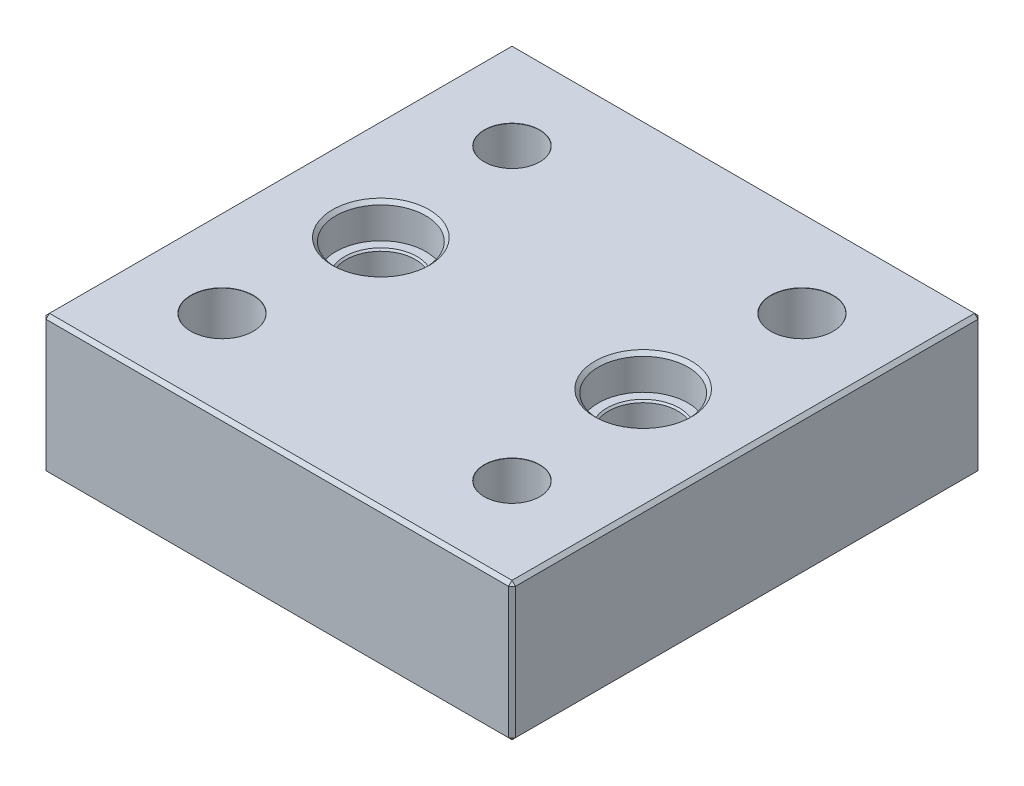
SolidWorks part; units mm, degrees
material "Plain Carbon Steel"
ref_plane "Front Plane" through (0, 0, 0) normal (0, 0, 1) x (1, 0, 0)
ref_plane "Top Plane" through (0, 0, 0) normal (0, 1, 0) x (1, 0, 0)
ref_plane "Right Plane" through (0, 0, 0) normal (1, 0, 0) x (0, 0, -1)
sketch "Sketch1" plane through (0, 0, 0) normal (0, 1, 0) x (1, 0, 0)
  line L1 (-34, 34) -> (34, 34)
  line L2 (-34, 34) -> (-34, -34)
  line L3 (-34, -34) -> (34, -34)
  line L4 (34, 34) -> (34, -34)
  line L5 (-34, 34) -> (34, -34) construction
  line L6 (-34, -34) -> (34, 34) construction
  point P0 (0, 0)
  dimension "D1" = 68
  dimension "D2" = 68
extrude "Boss-Extrude1" add sketch "Sketch1" against normal blind 20
sketch "Sketch2" plane through (0, 0, 0) normal (0, 1, 0) x (1, 0, 0)
  line L0 (-34, 0) -> (34, 0) construction
  line L1 (-34, 34) -> (-34, -34) construction
  line L2 (34, -34) -> (34, 34) construction
  line L3 (-34, -34) -> (34, -34) construction
  line L4 (0, 34) -> (0, -34) construction
  line L5 (34, 34) -> (-34, 34) construction
  circle A0 centre (-19, 0) radius 5
  circle A1 centre (19, 0) radius 5
  dimension "D2" = 10
  dimension "D1" = 38
extrude "Cut-Extrude1" cut sketch "Sketch2" against normal up to next
sketch "Sketch3" plane through (0, 0, 0) normal (0, 1, 0) x (1, 0, 0)
  circle A0 centre (-19, 0) radius 6.5
  circle A1 centre (19, 0) radius 6.5
  dimension "D1" = 13
extrude "Cut-Extrude2" cut sketch "Sketch3" against normal blind 5
chamfer "Chamfer2" distance 0.5 angle 45 12 edges at (34, -10, -34) (34, -20, 0) (0, -20, -34) (-34, -10, -34) (34, -10, 34) (0, -20, 34) (-34, -20, 0) (-34, -10, 34) (-34, 0, 0) (0, 0, 34) (34, 0, 0) (0, 0, -34)
chamfer "Chamfer4" distance 0.5 angle 45 2 edges at (19, 0, 6.5) (-19, 0, 6.5)
chamfer "Chamfer5" distance 0.25 angle 45 4 edges at (19, -20, 5) (-19, -20, 5) (19, -5, 5) (-19, -5, 5)
hole_wizard "CBORE for M8 Hex Socket Head Cap Screw1" positions "Sketch4" profile "Sketch5" counterbore size "M8" standard "ISO" end condition through all
sketch "Sketch4" plane through (0, -20, 0) normal (0, -1, 0) x (-1, 0, 0)
  line L0 (-34, -33.5) -> (-34, 33.5) construction
  line L1 (-33.5, 34) -> (33.5, 34) construction
  line L4 (34, 33.5) -> (34, -33.5) construction
  line L5 (33.5, -34) -> (-33.5, -34) construction
  point P2 (21, -21)
  point P6 (-21, 21)
  dimension "D1" = 13
  dimension "D2" = 13
  dimension "D3" = 13
  dimension "D4" = 13
sketch "Sketch5" plane through (-21, -20, 21) normal (1, 0, 0) x (0, 0, -1)
  line L0 (0, 0) -> (0, 20)
  line L1 (4.5, 19.975) -> (4.525, 20)
  line L2 (7.5, 8.6) -> (4.5, 8.6)
  line L3 (4.5, 8.6) -> (4.5, 19.975)
  line L5 (7.5, 8.6) -> (7.5, 0.025)
  line L6 (7.5, 0.025) -> (7.525, 0)
  line L7 (7.525, 0) -> (0, 0)
  line L8 (-7.5, 0.025) -> (-7.525, 0) construction
  line L11 (0, -6.35) -> (0, 107.95) construction
  line L12 (4.525, 20) -> (0, 20)
  line L13 (-4.5, 19.975) -> (-4.525, 20) construction
  dimension "Thru Hole Dia." = 9
  dimension "Thru Hole Depth" = 20
  dimension "C'Bore Dia." = 15
  dimension "C'Bore Depth" = 8.6
  dimension "Near C'Sink Dia." = 15.05
  dimension "Near C'Sink Angle" = 90
  dimension "Far C'Sink Dia." = 9.05
  dimension "Far C'Sink Angle" = 90
sketch "Sketch6" plane through (0, -20, 0) normal (0, -1, 0) x (-1, 0, 0)
  line L0 (-33.5, 34) -> (33.5, 34) construction
  line L1 (34, 33.5) -> (34, -33.5) construction
  line L2 (33.5, -34) -> (-33.5, -34) construction
  line L3 (-34, -33.5) -> (-34, 33.5) construction
  point P0 (21, 21)
  point P2 (-21, -21)
  dimension "D1" = 13
  dimension "D2" = 13
  dimension "D3" = 13
  dimension "D4" = 13
hole_wizard "Ø8.0mm Dowel Hole1" positions "Sketch6" profile "Sketch7" hole size "Ø8.0" standard "ISO" end condition through all
sketch "Sketch7" plane through (-21, -20, -21) normal (1, 0, 0) x (0, 0, -1)
  line L0 (0, 0) -> (0, 20)
  line L1 (0, 20) -> (4.025, 20)
  line L2 (4, 19.975) -> (4, 0.025)
  line L3 (4, 0.025) -> (4.025, 0)
  line L5 (4.025, 0) -> (0, 0)
  line L6 (-4, 0.025) -> (-4.025, 0) construction
  line L7 (4.025, 20) -> (4, 19.975)
  line L8 (-4.025, 20) -> (-4, 19.975) construction
  line L11 (0, -6.35) -> (0, 107.95) construction
  dimension "Thru Hole Dia." = 8
  dimension "Thru Hole Depth" = 20
  dimension "Near C'Sink Dia." = 8.05
  dimension "Near C'Sink Angle" = 90
  dimension "Far C'Sink Dia." = 8.05
  dimension "Far C'Sink Angle" = 90
